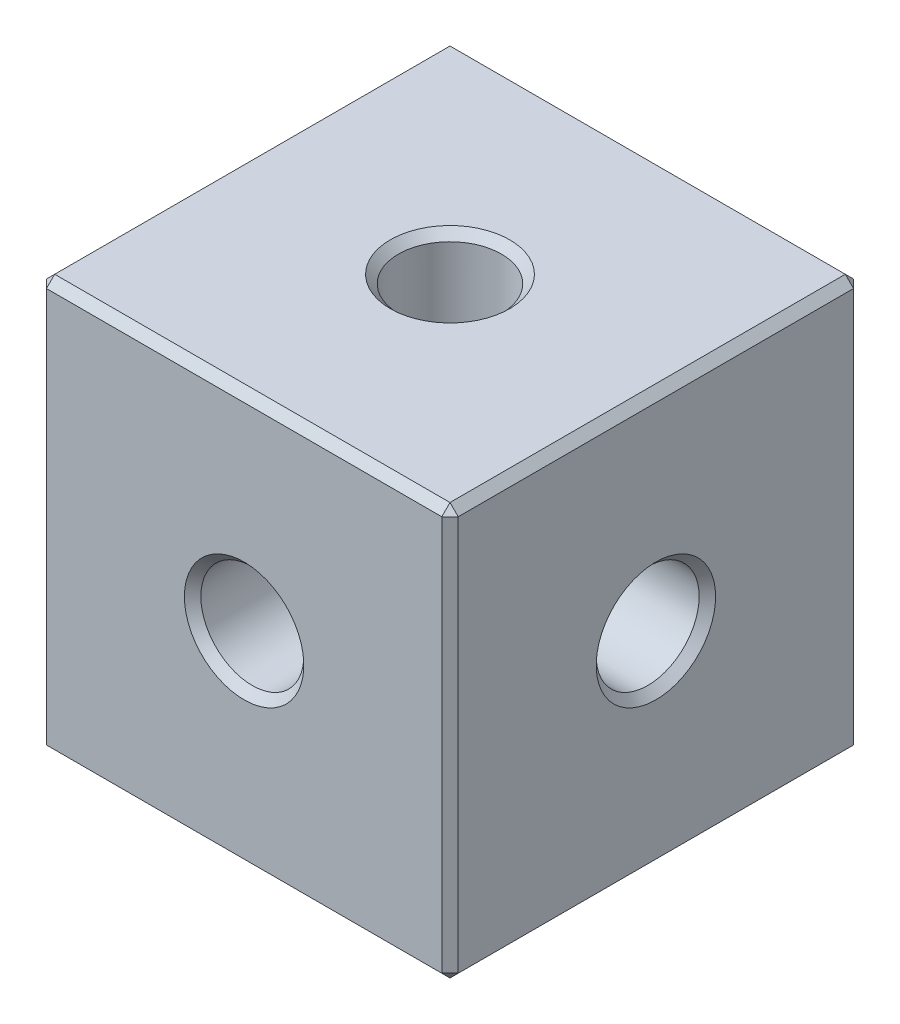
SolidWorks part; units mm, degrees
ref_plane "前视基准面" through (0, 0, 0) normal (0, 0, 1) x (1, 0, 0)
ref_plane "上视基准面" through (0, 0, 0) normal (0, 1, 0) x (1, 0, 0)
ref_plane "右视基准面" through (0, 0, 0) normal (1, 0, 0) x (0, 0, -1)
sketch "草图1" plane through (0, 0, 0) normal (0, 1, 0) x (1, 0, 0)
  line L1 (-5, 5) -> (5, 5)
  line L2 (-5, 5) -> (-5, -5)
  line L3 (-5, -5) -> (5, -5)
  line L4 (5, 5) -> (5, -5)
  line L5 (-5, 5) -> (5, -5) construction
  line L6 (-5, -5) -> (5, 5) construction
  point P0 (0, 0)
  dimension "D1" = 10
extrude "凸台-拉伸1" add sketch "草图1" along normal mid plane 10
hole_wizard "M3 螺纹孔1" positions "草图2" profile "草图3" tap size "M3" standard "GB" end condition through all
sketch "草图2" plane through (0, 0, 5) normal (0, 0, 1) x (1, 0, 0)
  point P0 (0, 0)
sketch "草图3" plane through (0, 0, 5) normal (1, 0, 0) x (0, -1, 0)
  line L0 (0, 0) -> (0, 10)
  line L1 (0, 10) -> (1.25, 10)
  line L2 (1.25, 10) -> (1.25, 0)
  line L5 (1.25, 0) -> (0, 0)
  line L11 (0, -6.35) -> (0, 107.95) construction
  dimension "通孔螺纹孔钻头直径" = 2.5
  dimension "通孔螺纹孔钻头深度" = 10
cosmetic thread "孔螺蚊线1" parameters "D2"=3
hole_wizard "M3 螺纹孔2" positions "草图4" profile "草图5" tap size "M3" standard "GB" end condition through all
sketch "草图4" plane through (0, 5, 0) normal (0, 1, 0) x (1, 0, 0)
  point P0 (0, 0)
sketch "草图5" plane through (0, 5, 0) normal (1, 0, 0) x (0, 0, 1)
  line L0 (0, 0) -> (0, 10)
  line L1 (0, 10) -> (1.25, 10)
  line L2 (1.25, 10) -> (1.25, 0)
  line L5 (1.25, 0) -> (0, 0)
  line L11 (0, -6.35) -> (0, 107.95) construction
  dimension "通孔螺纹孔钻头直径" = 2.5
  dimension "通孔螺纹孔钻头深度" = 10
cosmetic thread "孔螺蚊线2"
hole_wizard "M3 螺纹孔3" positions "草图6" profile "草图7" tap size "M3" standard "GB" end condition through all
sketch "草图6" plane through (5, 0, 0) normal (1, 0, 0) x (0, 0, -1)
  point P0 (0, 0)
sketch "草图7" plane through (5, 0, 0) normal (0, 1, 0) x (0, 0, -1)
  line L0 (0, 0) -> (0, 10)
  line L1 (0, 10) -> (1.25, 10)
  line L2 (1.25, 10) -> (1.25, 0)
  line L5 (1.25, 0) -> (0, 0)
  line L11 (0, -6.35) -> (0, 107.95) construction
  dimension "通孔螺纹孔钻头直径" = 2.5
  dimension "通孔螺纹孔钻头深度" = 10
cosmetic thread "孔螺蚊线3"
chamfer "倒角1" distance 0.2 angle 45 18 edges at (0, -5, 1.25) (-5, 0, -1.25) (1.25, 0, -5) (5, 0, -1.25) (1.25, 0, 5) (-5, -5, 0) (-5, 0, -5) (0, -5, -5) (5, 0, -5) (5, -5, 0) (-5, 0, 5) (0, -5, 5) (5, 0, 5) (0, 5, 5) (-5, 5, 0) (0, 5, -5) (5, 5, 0) (0, 5, 1.25)
